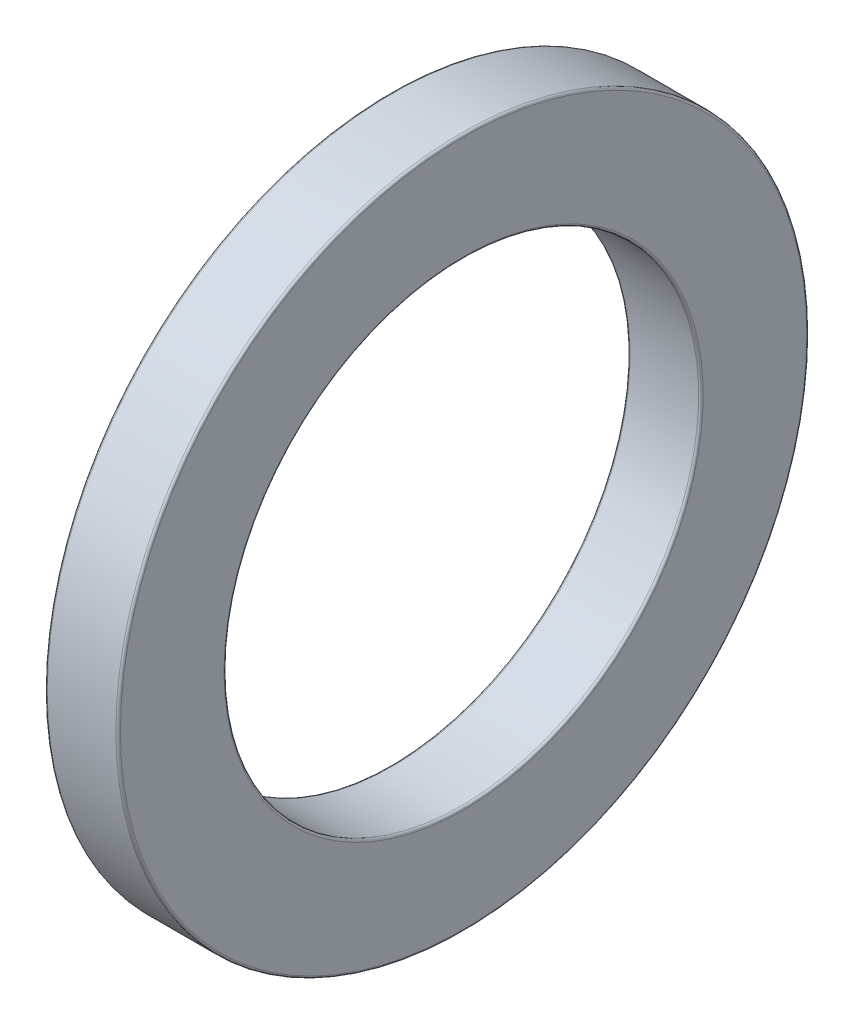
SolidWorks part; units mm, degrees
ref_plane "Alzado" through (0, 0, 0) normal (0, 0, 1) x (1, 0, 0)
ref_plane "Planta" through (0, 0, 0) normal (0, 1, 0) x (1, 0, 0)
ref_plane "Vista lateral" through (0, 0, 0) normal (1, 0, 0) x (0, 0, -1)
sketch "Croquis1" plane through (0, 0, 0) normal (0, 1, 0) x (1, 0, 0)
  line L0 (0, 0) -> (22.6391, 0) construction
  line L1 (0, 0) -> (0, 10.41) construction
  line L2 (0, 10.41) -> (1.505, 10.41)
  line L3 (167.9149, 358.0084) -> (1078.5816, 358.0084) construction
  line L4 (1.605, 10.51) -> (1.605, 15.05)
  line L9 (1.505, 15.15) -> (-1.505, 15.15)
  line L10 (-1.605, 15.05) -> (-1.605, 10.51)
  line L11 (-1.505, 10.41) -> (0, 10.41)
  arc A0 (-1.605, 10.51) -> (-1.505, 10.41) centre (-1.505, 10.51) ccw
  arc A1 (1.605, 10.51) -> (1.505, 10.41) centre (1.505, 10.51) cw
  arc A2 (1.505, 15.15) -> (1.605, 15.05) centre (1.505, 15.05) cw
  arc A3 (-1.505, 15.15) -> (-1.605, 15.05) centre (-1.505, 15.05) ccw
  point P11 (-1.605, 10.41)
  point P14 (1.605, 10.41)
  point P20 (-1.605, 15.15)
  dimension "D5" = 0.1
  dimension "D1" = 10.41
  dimension "D2" = 4.74
  dimension "D3" = 1.605
  dimension "D4" = 1.605
revolve "Revolución1" add sketch "Croquis1" angle 360 about L0
